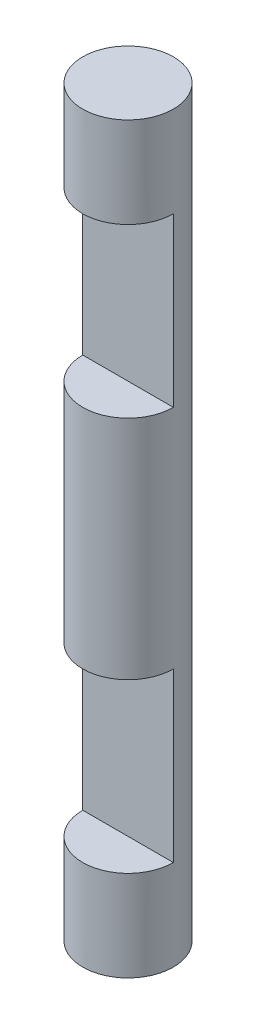
SolidWorks part; units mm, degrees
material "ABS"
ref_plane "Front Plane" through (0, 0, 0) normal (0, 0, 1) x (1, 0, 0)
ref_plane "Top Plane" through (0, 0, 0) normal (0, 1, 0) x (1, 0, 0)
ref_plane "Right Plane" through (0, 0, 0) normal (1, 0, 0) x (0, 0, -1)
sketch "Sketch1" plane through (0, 0, 0) normal (0, 1, 0) x (1, 0, 0)
  circle A0 centre (0, 0) radius 13
  dimension "D1" = 26
extrude "Boss-Extrude1" add sketch "Sketch1" along normal blind 1
ref_plane "Plane1" through (0, 1, 0) normal (0, 1, 0) x (1, 0, 0)
ref_plane "Plane2" through (0, 4.7, 0) normal (0, 1, 0) x (1, 0, 0)
ref_plane "Plane3" through (0, 9.7, 0) normal (0, 1, 0) x (1, 0, 0)
ref_plane "Plane4" through (0, 13.4, 0) normal (0, 1, 0) x (1, 0, 0)
ref_plane "Plane5" through (0, 18.4, 0) normal (0, 1, 0) x (1, 0, 0)
ref_plane "Plane6" through (0, 22.1, 0) normal (0, 1, 0) x (1, 0, 0)
ref_plane "Plane7" through (0, 27.1, 0) normal (0, 1, 0) x (1, 0, 0)
ref_plane "Plane8" through (0, 30.8, 0) normal (0, 1, 0) x (1, 0, 0)
sketch "Sketch16" plane through (0, 30.8, 0) normal (0, 1, 0) x (1, 0, 0)
  circle A0 centre (0, 0) radius 13
  circle A1 centre (0, 0) radius 13 construction
  dimension "D1" = 0
extrude "Boss-Extrude3" add sketch "Sketch16" along normal blind 1 separate body
sketch "Sketch18" plane through (0, 4.7, 0) normal (0, 1, 0) x (1, 0, 0)
  line L1 (-11, -11) -> (11, -11)
  line L2 (-11, -11) -> (-11, 11)
  line L3 (-11, 11) -> (11, 11)
  line L4 (11, -11) -> (11, 11)
  point P10 (-14.8124, 1.9257)
  dimension "D2" = 22
  dimension "D3" = 22
sketch "Sketch19" plane through (0, 1, 0) normal (0, 1, 0) x (1, 0, 0)
  circle A0 centre (0, 11) radius 1
  point P13 (0, 0)
  dimension "D1" = 2
  dimension "D2" = 11
extrude "Boss-Extrude4" add sketch "Sketch19" along normal up to surface (29.8 mm away) up to face at (0, 30.8, 13)
extrude "Cut-Extrude6" cut sketch "Sketch18" against normal blind 3.7
sketch "Sketch21" plane through (0, 13.4, 0) normal (0, 1, 0) x (1, 0, 0)
  line L1 (-11, -11) -> (11, -11)
  line L2 (-11, -11) -> (-11, 11)
  line L3 (-11, 11) -> (11, 11)
  line L4 (11, -11) -> (11, 11)
  dimension "D1" = 11
  dimension "D2" = 22
  dimension "D3" = 22
  dimension "D4" = 11
extrude "Cut-Extrude7" cut sketch "Sketch21" against normal blind 3.7
sketch "Sketch22" plane through (0, 22.1, 0) normal (0, 1, 0) x (1, 0, 0)
  circle A0 centre (0, 0) radius 11
  dimension "D1" = 22
extrude "Cut-Extrude8" cut sketch "Sketch22" against normal blind 3.7
sketch "Sketch23" plane through (0, 30.8, 0) normal (0, 1, 0) x (1, 0, 0)
  circle A0 centre (0, 0) radius 11
  dimension "D1" = 22
extrude "Cut-Extrude9" cut sketch "Sketch23" against normal blind 3.7
sketch "Sketch24" plane through (0, 31.8, 0) normal (0, 1, 0) x (1, 0, 0)
  circle A0 centre (0, 0) radius 19.9218
extrude "Cut-Extrude10" cut sketch "Sketch24" against normal blind 1
sketch "Sketch25" plane through (0, 1, 0) normal (0, 1, 0) x (1, 0, 0)
  circle A0 centre (0, 0) radius 36.1829
extrude "Cut-Extrude11" cut sketch "Sketch25" against normal blind 1
sketch "Sketch26" plane through (0, 30.8, 0) normal (0, 1, 0) x (1, 0, 0)
  circle A0 centre (0, 11) radius 1
  arc A1 (0.999, 10.9545) -> (-0.999, 10.9545) centre (0, 0) ccw construction
  arc A2 (0.999, 10.9545) -> (-0.999, 10.9545) centre (0, 11) ccw construction
  arc M1 (0.999, 10.9545) -> (-0.999, 10.9545) centre (0, 11) ccw
  arc M2 (-0.999, 10.9545) -> (0.999, 10.9545) centre (0, 0) cw
  dimension "D1" = 0
extrude "Boss-Extrude5" add sketch "Sketch26" along normal blind 2 contours M2 M1 | A0 M2
sketch "Sketch27" plane through (0, 1, 0) normal (0, -1, 0) x (1, 0, 0)
  circle A0 centre (0, -11) radius 1
extrude "Boss-Extrude6" add sketch "Sketch27" along normal blind 2
sketch "Sketch28" plane through (0, 32.8, 0) normal (0, 1, 0) x (1, 0, 0)
  circle A0 centre (0, 11) radius 9.6767
extrude "Cut-Extrude12" cut sketch "Sketch28" against normal offset from surface (17.4 mm away) 2 up to face at (0, 13.4, -10.5)
